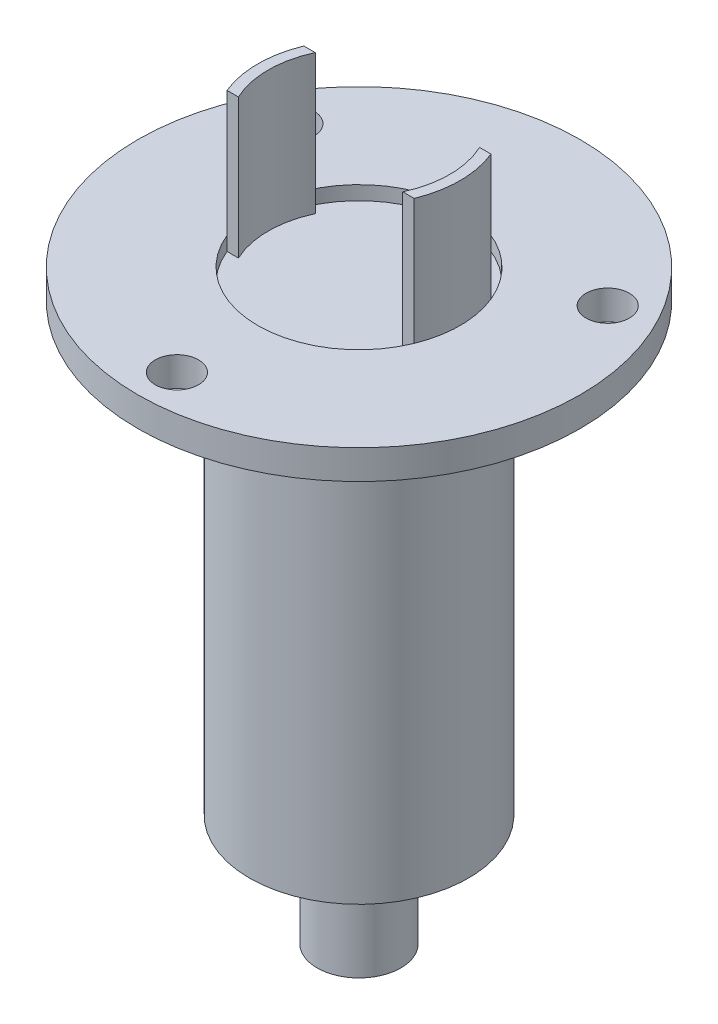
SolidWorks part; units mm, degrees
ref_plane "Front" through (0, 0, 0) normal (0, 0, 1) x (1, 0, 0)
ref_plane "Top" through (0, 0, 0) normal (0, 1, 0) x (1, 0, 0)
ref_plane "Right" through (0, 0, 0) normal (1, 0, 0) x (0, 0, -1)
sketch "草图1" plane through (0, 0, 0) normal (0, 0, 1) x (1, 0, 0)
  line L0 (0, 0) -> (0, 41.0818) construction
  line L2 (0, 0) -> (3, 0)
  line L3 (0, 0) -> (0, 8)
  line L4 (0, 8) -> (3, 8)
  line L5 (3, 0) -> (3, 8)
  line L6 (0, 8) -> (7.85, 8)
  line L7 (0, 8) -> (0, 39.9)
  line L8 (0, 39.9) -> (7.85, 39.9)
  line L9 (7.85, 8) -> (7.85, 39.9)
  line L10 (0, 39.9) -> (15.85, 39.9)
  line L11 (0, 39.9) -> (0, 42)
  line L12 (0, 42) -> (15.85, 42)
  line L13 (15.85, 39.9) -> (15.85, 42)
  dimension "D1" = 31.7
  dimension "D2" = 15.7
  dimension "D3" = 6
  dimension "D4" = 2.1
  dimension "D5" = 34
  dimension "D6" = 8
revolve "旋转1" add sketch "草图1" angle 360 about L0
sketch "草图2" plane through (0, 42, 0) normal (0, 1, 0) x (1, 0, 0)
  circle A0 centre (0, 0) radius 7.25
  dimension "D1" = 14.5
extrude "切除-拉伸1" cut sketch "草图2" against normal blind 1
sketch "草图3" plane through (0, 41, 0) normal (0, 1, 0) x (1, 0, 0)
  line L1 (-11.2273, 2.7526) -> (11.2273, 2.7526)
  line L2 (-11.2273, 2.7526) -> (-11.2273, -2.7526)
  line L3 (-11.2273, -2.7526) -> (11.2273, -2.7526)
  line L4 (11.2273, 2.7526) -> (11.2273, -2.7526)
  line L5 (-11.2273, 2.7526) -> (11.2273, -2.7526) construction
  line L6 (-11.2273, -2.7526) -> (11.2273, 2.7526) construction
  circle A0 centre (0, 0) radius 6.5
  circle A1 centre (0, 0) radius 7.25
  circle A2 centre (0, 0) radius 7.25
  circle M2 centre (0, 0) radius 7.25
  dimension "D2" = 13
  dimension "D1" = 0
extrude "凸台-拉伸1" add sketch "草图3" along normal blind 10 contours A0 L1 L3 M2 | A0 L3 L1 M2
sketch "草图4" plane through (0, 42, 0) normal (0, 1, 0) x (1, 0, 0)
  circle A0 centre (0, -13.05) radius 1.55
  circle A2 centre (0, 0) radius 15.85 construction
  circle A3 centre (-11.3016, 6.525) radius 1.55
  circle A4 centre (11.3016, 6.525) radius 1.55
  point P12 (0, 0)
  dimension "D1" = 3.1
  dimension "D2" = 1.25
  dimension "D3" = 3
extrude "切除-拉伸2" cut sketch "草图4" against normal through all both and the other way through all
